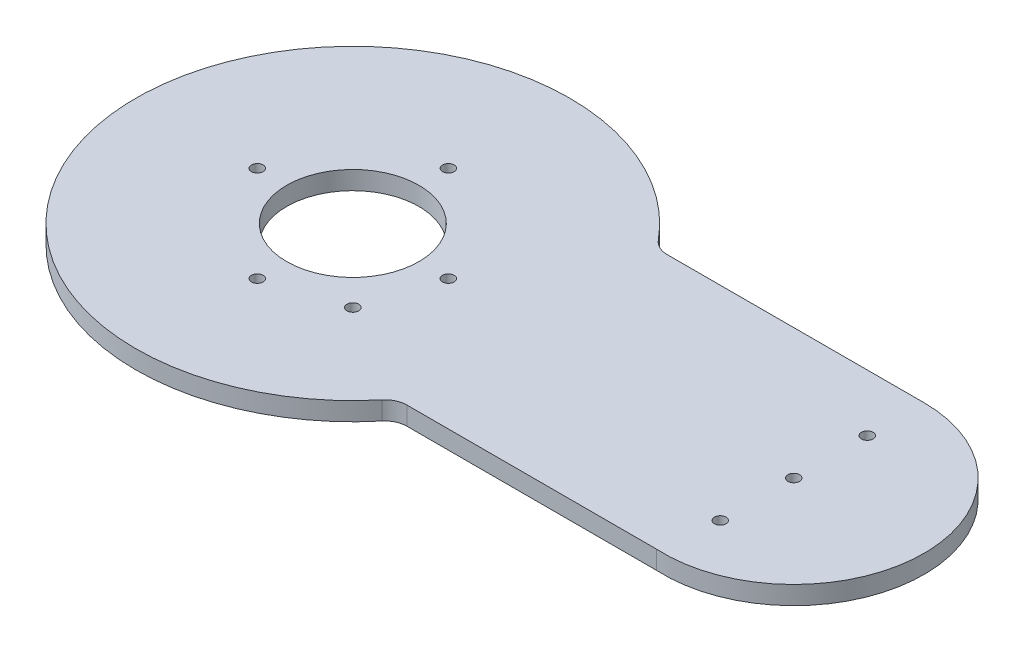
SolidWorks part; units mm, degrees
ref_plane "Front" through (0, 0, 0) normal (0, 0, 1) x (1, 0, 0)
ref_plane "Top" through (0, 0, 0) normal (0, 1, 0) x (1, 0, 0)
ref_plane "Right" through (0, 0, 0) normal (1, 0, 0) x (0, 0, -1)
sketch "Sketch1" plane through (0, 0, 0) normal (0, 1, 0) x (1, 0, 0)
  line L0 (77.4, 0) -> (-75, 0) construction
  line L1 (75, -45) -> (-14.9986, -45)
  line L2 (77.4, 45.064) -> (-14.9986, 45)
  arc A0 (75, -45) -> (77.4, 45.064) centre (77.4, 0) ccw
  circle A2 centre (-75, 0) radius 22.098 construction
  circle A3 centre (77.4, 0) radius 2.0193
  arc A4 (-14.9986, 45) -> (-14.9986, -45) centre (-75, 0) ccw
  point P3 (0, 0)
  dimension "D1" = 152.4
  dimension "D3" = 44.196
  dimension "D4" = 4.0386
  dimension "D5" = 75.0011
extrude "Boss-Extrude1" add sketch "Sketch1" along normal blind 6.35
hole_wizard "M3x0.5 Tapped Hole1" [suppressed] positions "Sketch5" profile "Sketch4" tap size "M3x0.5" standard "ANSI Metric"
sketch "Sketch5" plane through (0, 6.35, 0) normal (0, 1, 0) x (1, 0, 0)
  circle A0 centre (-75, 0) radius 27
  point P0 (-75, -27)
  point P3 (-102, 0)
  point P6 (-75, 27)
  point P9 (-48, 0)
  dimension "D1" = 54
sketch "Sketch4" plane through (-75, 6.35, 27) normal (1, 0, 0) x (0, 0, 1)
  line L0 (0, 0) -> (0, 6.35)
  line L1 (0, 6.35) -> (1.25, 6.35)
  line L2 (1.25, 6.35) -> (1.25, 0)
  line L5 (1.25, 0) -> (0, 0)
  line L11 (0, -6.35) -> (0, 107.95) construction
  dimension "Thru Tap Drill Dia." = 2.5
  dimension "Thru Tap Drill Depth" = 6.35
cosmetic thread "Hole Thread1" [suppressed] parameters "D2"=3
cosmetic thread "Hole Thread2" [suppressed] parameters "D2"=3
cosmetic thread "Hole Thread3" [suppressed] parameters "D2"=3
cosmetic thread "Hole Thread4" [suppressed] parameters "D2"=3
hole_wizard "M3 Clearance Slot1" [suppressed] positions "Sketch11" profile "Sketch10" size "M3" standard "ANSI Metric"
sketch "Sketch11" plane through (0, 6.35, 0) normal (0, 1, 0) x (1, 0, 0)
  line L0 (-50, -30) -> (-20, -30) construction
  line L1 (-75, 0) -> (75, 0) construction
  circle A0 centre (-75, 0) radius 22.098 construction
  point P0 (-35, -30)
  dimension "D1" = 30
  dimension "D2" = 40
  dimension "D3" = 30
sketch "Sketch10" plane through (-35, 6.35, 30) normal (1, 0, 0) x (0, 0, 1)
  line L0 (0, 0) -> (0, 26.4215)
  line L1 (0, 26.4215) -> (1.7, 25.4)
  line L2 (1.7, 25.4) -> (1.7, 0)
  line L5 (1.7, 0) -> (0, 0)
  line L10 (0, 26.4215) -> (-1.7, 25.4) construction
  line L11 (0, -6.35) -> (0, 107.95) construction
  dimension "Hole Dia." = 3.4
  dimension "Hole Depth" = 25.4
  dimension "Drill Angle" = 118
hole_wizard "M3x0.5 Tapped Hole3" [suppressed] positions "Sketch13" profile "Sketch14" tap size "M3x0.5" standard "ANSI Metric"
sketch "Sketch13" plane through (0, 0, 0) normal (0, -1, 0) x (-1, 0, 0)
  point P0 (21.7, 30)
sketch "Sketch14" plane through (-21.7, 0, -30) normal (1, 0, 0) x (0, 0, -1)
  line L0 (0, 0) -> (0, 6.35)
  line L1 (0, 6.35) -> (1.25, 6.35)
  line L2 (1.25, 6.35) -> (1.25, 0)
  line L5 (1.25, 0) -> (0, 0)
  line L11 (0, -6.35) -> (0, 107.95) construction
  dimension "Thru Tap Drill Dia." = 2.5
  dimension "Thru Tap Drill Depth" = 6.35
cosmetic thread "Hole Thread7" [suppressed] parameters "D2"=3
extrude "Cut-Extrude1" cut sketch "Sketch16" against normal blind 6.35
sketch "Sketch16" plane through (0.9648, 6.35, 105.9343) normal (0, 1, 0) x (-1, 0, 0)
  circle A6 centre (75.9648, -105.9343) radius 22.86
  circle A7 centre (50.801, -80.7705) radius 2.0193
  circle A8 centre (42.9448, -105.9343) radius 2.0193
  circle A9 centre (75.9648, -72.9143) radius 2.0193
  circle A10 centre (108.9848, -105.9343) radius 2.0193
  circle A11 centre (75.9648, -138.9543) radius 2.0193
fillet "Fillet1" radius 7.62 2 edges at (-14.9986, 3.175, 45) (-14.9986, 3.175, -45)
hole_wizard "#21 (0.159) Diameter Hole1" positions "Sketch17" profile "Sketch18" hole size "#21" standard "ANSI Inch" end condition through all
sketch "Sketch17" plane through (0, 6.35, 0) normal (0, 1, 0) x (1, 0, 0)
  line L0 (77.4, -25.4) -> (77.4, 25.4) construction
  circle A3 centre (77.4, 0) radius 2.0193 construction
  circle A4 centre (77.4, 0) radius 2.0193 construction
  point P0 (77.4, 25.4)
  point P2 (77.4, -25.4)
  point P23 (0, 0)
  point P24 (77.4, 0)
  dimension "D1" = 50.8
sketch "Sketch18" plane through (77.4, 6.35, -25.4) normal (1, 0, 0) x (0, 0, 1)
  line L0 (0, 0) -> (0, 6.35)
  line L1 (0, 6.35) -> (2.0193, 6.35)
  line L2 (2.0193, 6.35) -> (2.0193, 0)
  line L5 (2.0193, 0) -> (0, 0)
  line L11 (0, -6.35) -> (0, 107.95) construction
  dimension "Thru Hole Dia." = 4.0386
  dimension "Thru Hole Depth" = 6.35
